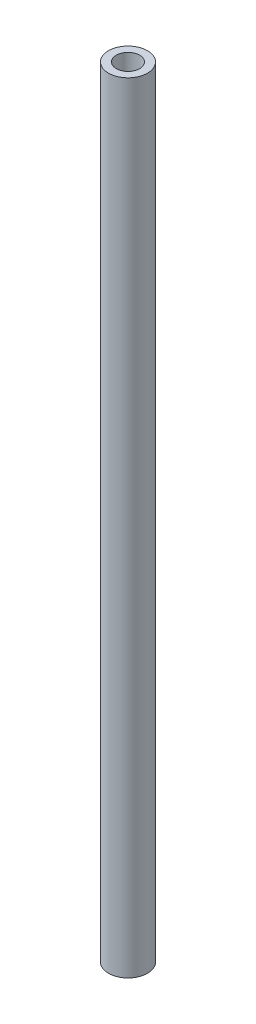
SolidWorks part; units mm, degrees
ref_plane "前视基准面" through (0, 0, 0) normal (0, 0, 1) x (1, 0, 0)
ref_plane "上视基准面" through (0, 0, 0) normal (0, 1, 0) x (1, 0, 0)
ref_plane "右视基准面" through (0, 0, 0) normal (1, 0, 0) x (0, 0, -1)
sketch "草图1" plane through (0, 0, 0) normal (0, 1, 0) x (1, 0, 0)
  circle A0 centre (0, 0) radius 2.5
  circle A1 centre (0, 0) radius 1.5
  dimension "D1" = 3
  dimension "D2" = 5
extrude "凸台-拉伸1" add sketch "草图1" along normal blind 100
